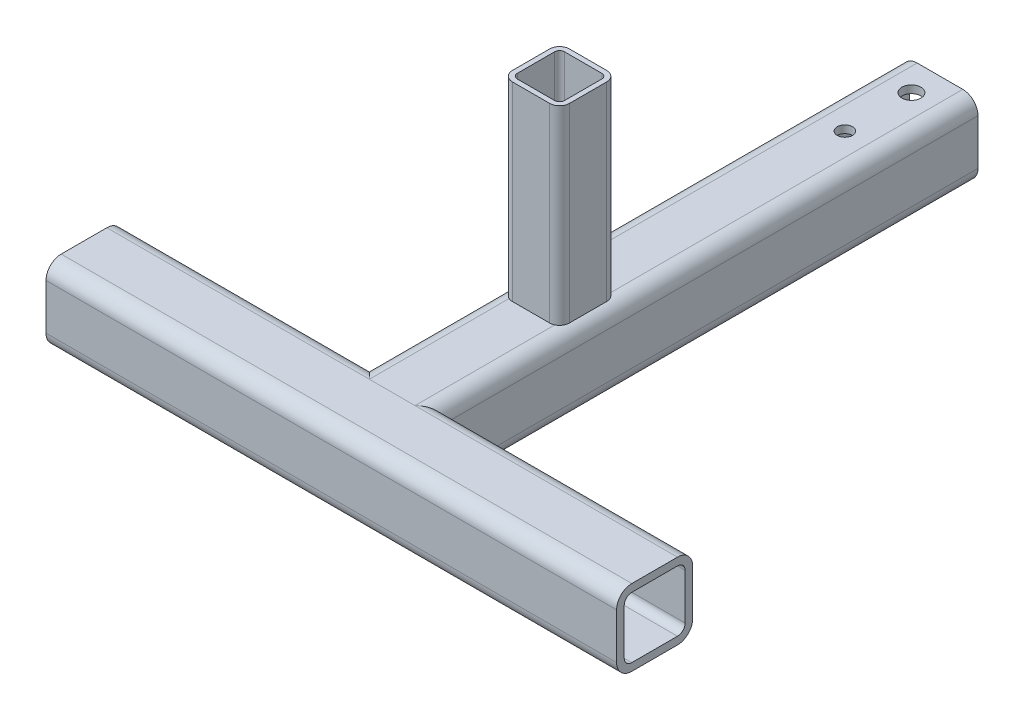
SolidWorks part; units mm, degrees
ref_plane "Plano frontal" through (0, 0, 0) normal (0, 0, 1) x (1, 0, 0)
ref_plane "Plano superior" through (0, 0, 0) normal (0, 1, 0) x (1, 0, 0)
ref_plane "Plano direito" through (0, 0, 0) normal (1, 0, 0) x (0, 0, -1)
sketch "Esboço1" plane through (0, 0, 0) normal (0, 1, 0) x (1, 0, 0)
  line L0 (0, 0) -> (0, 300)
  line L1 (-150, 0) -> (150, 0)
  point P5 (0, 0)
  dimension "D1" = 300
  dimension "D2" = 300
ref_plane "Plano1" through (-150, 0, 0) normal (1, 0, 0) x (0, 0, -1)
other "Square tube - configured 40 X 40 X 4(1)"
ref_plane "Plano2" through (-150, 0, 0) normal (1, 0, 0) x (0, 0, -1)
sketch "Sketch11" plane through (-150, 0, 0) normal (1, 0, 0) x (0, 0, -1)
  line L0 (-12, -16) -> (12, -16)
  line L1 (-16, -12) -> (-16, 12)
  line L2 (12, 16) -> (-12, 16)
  line L3 (16, 12) -> (16, -12)
  line L4 (-12, -20) -> (12, -20)
  line L5 (-20, -12) -> (-20, 12)
  line L6 (12, 20) -> (-12, 20)
  line L7 (20, 12) -> (20, -12)
  arc A0 (20, 12) -> (12, 20) centre (12, 12) ccw
  arc A1 (12, -20) -> (20, -12) centre (12, -12) ccw
  arc A2 (-20, -12) -> (-12, -20) centre (-12, -12) ccw
  arc A3 (-12, 20) -> (-20, 12) centre (-12, 12) ccw
  arc A4 (-12, 16) -> (-16, 12) centre (-12, 12) ccw
  arc A5 (16, 12) -> (12, 16) centre (12, 12) ccw
  arc A6 (12, -16) -> (16, -12) centre (12, -12) ccw
  arc A7 (-16, -12) -> (-12, -16) centre (-12, -12) ccw
  point P0 (-20, 0)
  point P1 (20, 0)
  point P2 (0, 20)
  point P3 (0, -20)
  point P4 (0, 0)
  point P5 (-20, -20)
  point P6 (20, -20)
  point P7 (20, 20)
  point P8 (-20, 20)
  point P33 (0, 0)
  dimension "D1" = 8
  dimension "Thickness" = 4
  dimension "V_leg" = 40
other "Square tube - configured 40 X 40 X 4(2)"
ref_plane "Plano3" through (0, 0, 0) normal (0, 0, -1) x (-1, 0, 0)
sketch "Sketch1" plane through (0, 0, 0) normal (0, 0, -1) x (-1, 0, 0)
  line L0 (-12, -16) -> (12, -16)
  line L1 (-16, -12) -> (-16, 12)
  line L2 (12, 16) -> (-12, 16)
  line L3 (16, 12) -> (16, -12)
  line L4 (-12, -20) -> (12, -20)
  line L5 (-20, -12) -> (-20, 12)
  line L6 (12, 20) -> (-12, 20)
  line L7 (20, 12) -> (20, -12)
  arc A0 (20, 12) -> (12, 20) centre (12, 12) ccw
  arc A1 (12, -20) -> (20, -12) centre (12, -12) ccw
  arc A2 (-20, -12) -> (-12, -20) centre (-12, -12) ccw
  arc A3 (-12, 20) -> (-20, 12) centre (-12, 12) ccw
  arc A4 (-12, 16) -> (-16, 12) centre (-12, 12) ccw
  arc A5 (16, 12) -> (12, 16) centre (12, 12) ccw
  arc A6 (12, -16) -> (16, -12) centre (12, -12) ccw
  arc A7 (-16, -12) -> (-12, -16) centre (-12, -12) ccw
  point P0 (-20, 0)
  point P1 (20, 0)
  point P2 (0, 20)
  point P3 (0, -20)
  point P4 (0, 0)
  point P5 (-20, -20)
  point P6 (20, -20)
  point P7 (20, 20)
  point P8 (-20, 20)
  point P33 (0, 0)
  dimension "D1" = 8
  dimension "Thickness" = 4
  dimension "V_leg" = 40
other "Aparar/Estender1"
sketch "Esboço5" plane through (0, 0, 0) normal (1, 0, 0) x (0, 0, -1)
  line L0 (100, 120) -> (100, 20)
  line L1 (300, 20) -> (12, 20) construction
  dimension "D1" = 100
  dimension "D2" = 100
other "Square tube - configured 30 X 30 X 2.6(1)"
ref_plane "Plano4" through (0, 120, -100) normal (0, -1, 0) x (0, 0, -1)
sketch "Sketch13" plane through (0, 120, -100) normal (0, -1, 0) x (0, 0, -1)
  line L0 (-9.8, -12.4) -> (9.8, -12.4)
  line L1 (-12.4, -9.8) -> (-12.4, 9.8)
  line L2 (9.8, 12.4) -> (-9.8, 12.4)
  line L3 (12.4, 9.8) -> (12.4, -9.8)
  line L4 (-9.8, -15) -> (9.8, -15)
  line L5 (-15, -9.8) -> (-15, 9.8)
  line L6 (9.8, 15) -> (-9.8, 15)
  line L7 (15, 9.8) -> (15, -9.8)
  arc A0 (15, 9.8) -> (9.8, 15) centre (9.8, 9.8) ccw
  arc A1 (9.8, -15) -> (15, -9.8) centre (9.8, -9.8) ccw
  arc A2 (-15, -9.8) -> (-9.8, -15) centre (-9.8, -9.8) ccw
  arc A3 (-9.8, 15) -> (-15, 9.8) centre (-9.8, 9.8) ccw
  arc A4 (-9.8, 12.4) -> (-12.4, 9.8) centre (-9.8, 9.8) ccw
  arc A5 (12.4, 9.8) -> (9.8, 12.4) centre (9.8, 9.8) ccw
  arc A6 (9.8, -12.4) -> (12.4, -9.8) centre (9.8, -9.8) ccw
  arc A7 (-12.4, -9.8) -> (-9.8, -12.4) centre (-9.8, -9.8) ccw
  point P0 (-15, 0)
  point P1 (15, 0)
  point P2 (0, 15)
  point P3 (0, -15)
  point P4 (0, 0)
  point P5 (-15, -15)
  point P6 (15, -15)
  point P7 (15, 15)
  point P8 (-15, 15)
  point P33 (0, 0)
  dimension "D1" = 5.2
  dimension "Thickness" = 2.6
  dimension "V_leg" = 30
sketch "Esboço8" plane through (0, 20, 0) normal (0, 1, 0) x (1, 0, 0)
  line L0 (0, 300) -> (0, 250) construction
  line L1 (-12, 300) -> (12, 300) construction
  circle A0 centre (0, 285) radius 5
  circle A2 centre (0, 250) radius 4
  point P6 (0, 241.0626)
  point P8 (0, 222.5525)
  dimension "D1" = 10
  dimension "D2" = 15
  dimension "D3" = 8
  dimension "D4" = 35
extrude "Corte-extrusão1" cut sketch "Esboço8" against normal through all and the other way through all
